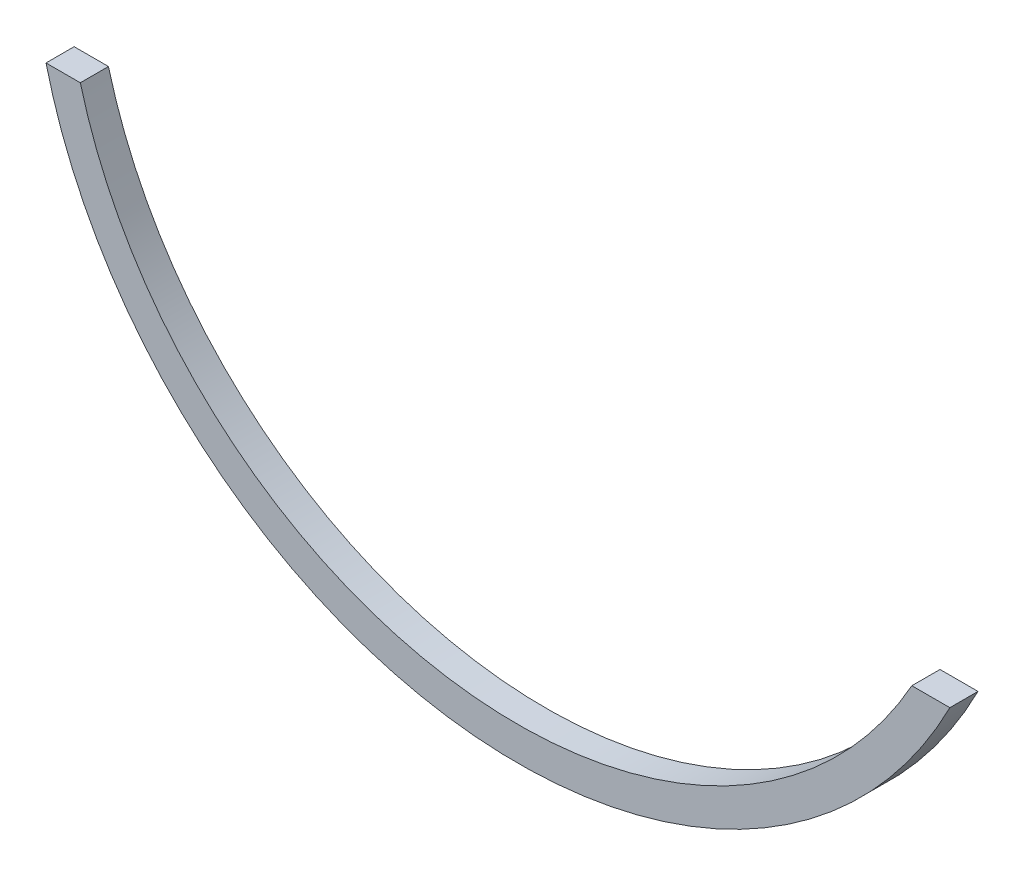
SolidWorks part; units mm, degrees
material "Hexcel AS4C (3000 Filaments)"
ref_plane "Front Plane" through (0, 0, 0) normal (0, 0, 1) x (1, 0, 0)
ref_plane "Top Plane" through (0, 0, 0) normal (0, 1, 0) x (1, 0, 0)
ref_plane "Right Plane" through (0, 0, 0) normal (1, 0, 0) x (0, 0, -1)
sketch "Sketch1" plane through (0, 0, 0) normal (0, 0, 1) x (1, 0, 0)
  line L0 (88.9044, -50) -> (97.4751, -50) construction
  line L1 (-106.3685, -26) -> (-98.6306, -26) construction
  line L2 (88.9044, -50) -> (97.4751, -50)
  line L3 (-106.3685, -26) -> (-98.6306, -26)
  circle A0 centre (0, 0) radius 109.5 construction
  circle A1 centre (0, 0) radius 102 construction
  circle A2 centre (0, 0) radius 109.5 construction
  circle A3 centre (0, 0) radius 102 construction
  arc A4 (-98.6306, -26) -> (88.9044, -50) centre (0, 0) ccw
  arc A6 (-106.3685, -26) -> (97.4751, -50) centre (0.0184, -0.0755) ccw
extrude "Boss-Extrude1" add sketch "Sketch1" along normal mid plane 6.35
